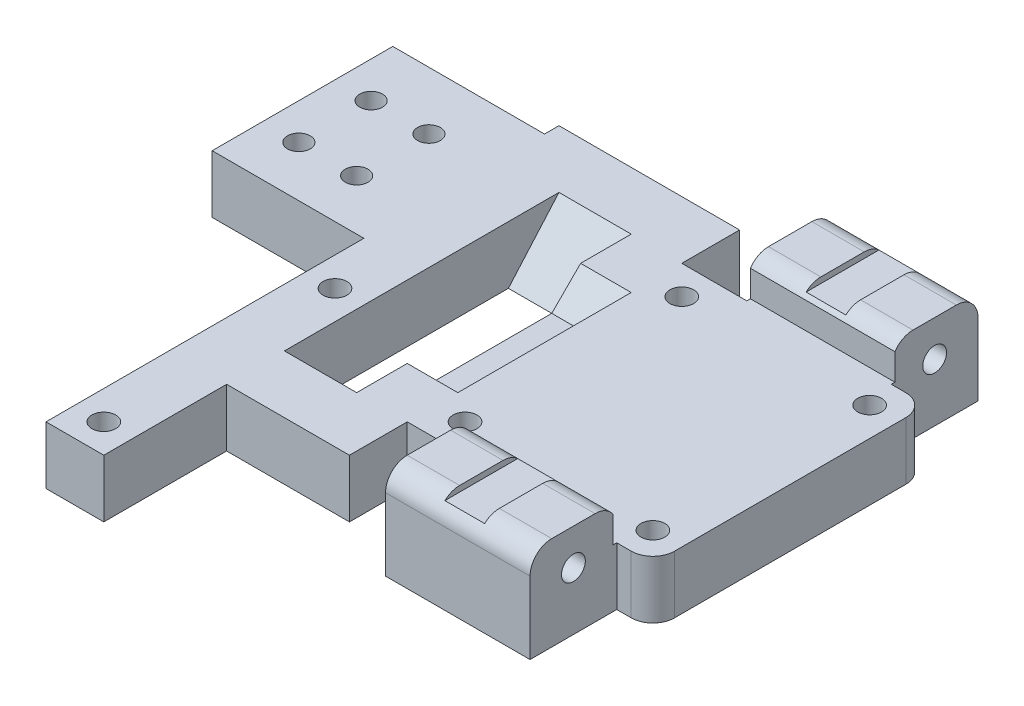
SolidWorks part; units mm, degrees
ref_plane "Front" through (0, 0, 0) normal (0, 0, 1) x (1, 0, 0)
ref_plane "Top" through (0, 0, 0) normal (0, 1, 0) x (1, 0, 0)
ref_plane "Right" through (0, 0, 0) normal (1, 0, 0) x (0, 0, -1)
sketch "Sketch1" plane through (0, 0, 0) normal (0, 1, 0) x (1, 0, 0)
  line L1 (0, 0) -> (300, 0)
  line L2 (0, 0) -> (0, -20)
  line L3 (0, -20) -> (300, -20)
  line L4 (300, 0) -> (300, -20)
  dimension "D1" = 20
  dimension "D2" = 300
extrude "Boss-Extrude1" add sketch "Sketch1" along normal blind 8
sketch "Sketch2" plane through (0, 0, 20) normal (0, 0, 1) x (1, 0, 0)
  line L0 (0, 8) -> (300, 8) construction
  line L1 (0, 0) -> (34, 0)
  line L2 (0, 0) -> (0, 8)
  line L3 (0, 8) -> (34, 8)
  line L4 (34, 0) -> (34, 8)
  line L5 (266, 8) -> (300, 8)
  line L6 (300, 0) -> (300, 8)
  line L7 (266, 0) -> (300, 0)
  line L8 (266, 0) -> (266, 8)
  dimension "D1" = 34
  dimension "D2" = 2
extrude "Boss-Extrude2" add sketch "Sketch2" along normal blind 9
sketch "Sketch3" plane through (0, 0, 0) normal (0, 0, -1) x (-1, 0, 0)
  line L0 (-300, 8) -> (0, 8) construction
  line L1 (0, 0) -> (-34, 0)
  line L2 (0, 0) -> (0, 8)
  line L3 (0, 8) -> (-34, 8)
  line L4 (-34, 0) -> (-34, 8)
  line L5 (-300, 0) -> (-300, 8)
  line L6 (-266, 8) -> (-300, 8)
  line L7 (-266, 0) -> (-266, 8)
  line L8 (-266, 0) -> (-300, 0)
  dimension "D1" = 34
  dimension "D2" = 2
extrude "Boss-Extrude3" add sketch "Sketch3" along normal blind 9
sketch "Sketch4" plane through (0, 8, 0) normal (0, 1, 0) x (1, 0, 0)
  line L0 (0, 9) -> (34, 9) construction
  line L1 (0, 9) -> (0, -29) construction
  circle A0 centre (4, 5) radius 1.65
  circle A1 centre (30, 5) radius 1.65
  circle A2 centre (30, -25) radius 1.65
  circle A3 centre (4, -25) radius 1.65
  circle A4 centre (296, -25) radius 1.65
  circle A5 centre (296, 5) radius 1.65
  circle A6 centre (270, -25) radius 1.65
  circle A7 centre (270, 5) radius 1.65
  dimension "D1" = 3.3
  dimension "D2" = 4
  dimension "D3" = 4
  dimension "D4" = 2
  dimension "D5" = 2
  dimension "D6" = 2
extrude "Cut-Extrude1" cut sketch "Sketch4" against normal through all
sketch "Sketch5" plane through (0, 0, 20) normal (0, 0, 1) x (1, 0, 0)
  line L0 (34, 8) -> (266, 8) construction
  line L1 (266, 0) -> (241, 0)
  line L2 (266, 0) -> (266, 8)
  line L3 (266, 8) -> (241, 8)
  line L4 (241, 0) -> (241, 8)
  dimension "D1" = 25
extrude "Boss-Extrude4" add sketch "Sketch5" along normal blind 17
sketch "Sketch6" plane through (0, 0, 0) normal (0, 0, -1) x (-1, 0, 0)
  line L0 (-266, 0) -> (-34, 0) construction
  line L1 (-266, 8) -> (-241, 8)
  line L2 (-266, 8) -> (-266, 0)
  line L3 (-266, 0) -> (-241, 0)
  line L4 (-241, 8) -> (-241, 0)
  dimension "D1" = 25
extrude "Boss-Extrude5" add sketch "Sketch6" along normal blind 17
sketch "Sketch7" plane through (0, 8, 0) normal (0, 1, 0) x (1, 0, 0)
  line L0 (266, -37) -> (241, -37) construction
  line L1 (259, -29) -> (249, -29)
  line L2 (259, -29) -> (259, 9)
  line L3 (259, 9) -> (249, 9)
  line L4 (249, -29) -> (249, 9)
  line L5 (241, -37) -> (241, -20) construction
  dimension "D1" = 10
  dimension "D2" = 38
  dimension "D3" = 8
  dimension "D4" = 8
extrude "Cut-Extrude2" cut sketch "Sketch7" against normal through all
sketch "Sketch8" plane through (0, 8, 0) normal (0, 1, 0) x (1, 0, 0)
  line L0 (259, -29) -> (259, 9) construction
  line L1 (259, -18) -> (266, -18)
  line L2 (259, -18) -> (259, -2)
  line L3 (259, -2) -> (266, -2)
  line L4 (266, -18) -> (266, -2)
  line L5 (266, -37) -> (241, -37) construction
  dimension "D1" = 7
  dimension "D2" = 16
  dimension "D3" = 19
extrude "Cut-Extrude3" cut sketch "Sketch8" against normal blind 4
sketch "Sketch9" plane through (259, 0, 0) normal (-1, 0, 0) x (0, 0, 1)
  line L0 (18, 4) -> (22, 8)
  line L1 (29, 8) -> (18, 8) construction
  line L2 (22, 8) -> (18, 8)
  line L3 (18, 8) -> (18, 4)
  line L4 (2, 4) -> (-2, 8)
  line L5 (2, 8) -> (-9, 8) construction
  line L6 (-2, 8) -> (2, 8)
  line L7 (2, 8) -> (2, 4)
  dimension "D1" = 4
  dimension "D2" = 4
extrude "Cut-Extrude4" cut sketch "Sketch9" against normal blind 7
sketch "Sketch10" plane through (259, 0, 0) normal (-1, 0, 0) x (0, 0, 1)
  line L0 (-9, 8) -> (-2, 0)
  line L1 (29, 0) -> (-9, 0) construction
  line L2 (-2, 0) -> (-9, 0)
  line L3 (-9, 0) -> (-9, 8)
  line L4 (29, 8) -> (22, 0)
  line L5 (22, 0) -> (29, 0)
  line L6 (29, 0) -> (29, 8)
  line L7 (-51.4523, 12.1971) -> (-51.8778, 12.5861)
  line M6 (-9, 8) -> (-9, 0)
  line M7 (-9, 0) -> (29, 0)
  line M8 (29, 0) -> (29, 8)
  dimension "D1" = 7
  dimension "D2" = 7
extrude "Boss-Extrude6" add sketch "Sketch10" along normal blind 10 contours L0 M6 M7 | L4 M8 M7
sketch "Sketch12" plane through (0, 0, 37) normal (0, 0, 1) x (1, 0, 0)
  line L0 (241, 0) -> (266, 0) construction
  line L1 (241, 8) -> (249, 8)
  line L2 (241, 8) -> (241, 0)
  line L3 (241, 0) -> (249, 0)
  line L4 (249, 8) -> (249, 0)
  dimension "D1" = 8
extrude "Boss-Extrude7" add sketch "Sketch12" along normal blind 17
sketch "Sketch13" plane through (0, 8, 0) normal (0, 1, 0) x (1, 0, 0)
  line L0 (249, -54) -> (241, -54) construction
  line L1 (249, -54) -> (249, -37) construction
  circle A0 centre (245, -50) radius 1.65
  circle A1 centre (245, -18) radius 1.65
  dimension "D1" = 3.3
  dimension "D2" = 4
  dimension "D3" = 4
  dimension "D4" = 2
extrude "Cut-Extrude6" cut sketch "Sketch13" against normal through all
sketch "Sketch14" plane through (0, 0, 29) normal (0, 0, 1) x (1, 0, 0)
  line L1 (295, 13) -> (275, 13)
  line L2 (295, 13) -> (295, 0)
  line L3 (295, 0) -> (275, 0)
  line L4 (275, 13) -> (275, 0)
  line L5 (266, 0) -> (300, 0) construction
  line L7 (266, 8) -> (266, 0) construction
  dimension "D1" = 20
  dimension "D2" = 9
  dimension "D3" = 13
extrude "Boss-Extrude8" add sketch "Sketch14" along normal blind 12
sketch "Sketch15" plane through (295, 0, 0) normal (1, 0, 0) x (0, 0, -1)
  line L0 (-41, 0) -> (-41, 13) construction
  line L1 (-41, 13) -> (-29, 13) construction
  circle A0 centre (-35, 8) radius 1.65
  dimension "D1" = 3.3
  dimension "D2" = 6
  dimension "D3" = 5
extrude "Cut-Extrude7" cut sketch "Sketch15" against normal blind 20
sketch "Sketch16" plane through (0, 0, -9) normal (0, 0, -1) x (-1, 0, 0)
  line L1 (-295, 13) -> (-275, 13)
  line L2 (-295, 13) -> (-295, 0)
  line L3 (-295, 0) -> (-275, 0)
  line L4 (-275, 13) -> (-275, 0)
  line L5 (-300, 0) -> (-266, 0) construction
  line L6 (-266, 0) -> (-266, 8) construction
  dimension "D1" = 20
  dimension "D2" = 9
  dimension "D3" = 13
extrude "Boss-Extrude9" add sketch "Sketch16" along normal blind 12
sketch "Sketch17" plane through (295, 0, 0) normal (1, 0, 0) x (0, 0, -1)
  line L1 (21, 13) -> (21, 0) construction
  line L2 (21, 13) -> (9, 13) construction
  circle A0 centre (15, 8) radius 1.65
  dimension "D1" = 3.3
  dimension "D3" = 6
  dimension "D2" = 5
extrude "Cut-Extrude8" cut sketch "Sketch17" against normal blind 20
sketch "Sketch18" plane through (0, 0, -9) normal (0, 0, -1) x (-1, 0, 0)
  line L1 (-25, 13) -> (-5, 13)
  line L2 (-25, 13) -> (-25, 0)
  line L3 (-25, 0) -> (-5, 0)
  line L4 (-5, 13) -> (-5, 0)
  line L5 (-34, 0) -> (0, 0) construction
  line L6 (-34, 8) -> (-34, 0) construction
  dimension "D1" = 20
  dimension "D2" = 9
  dimension "D3" = 13
extrude "Boss-Extrude10" add sketch "Sketch18" along normal blind 12
sketch "Sketch19" plane through (5, 0, 0) normal (-1, 0, 0) x (0, 0, 1)
  line L0 (-21, 0) -> (-21, 13) construction
  line L1 (-21, 13) -> (-9, 13) construction
  circle A0 centre (-15, 8) radius 1.6
  dimension "D1" = 3.2
  dimension "D2" = 6
  dimension "D3" = 5
extrude "Cut-Extrude9" cut sketch "Sketch19" against normal blind 20
sketch "Sketch20" plane through (0, 0, 29) normal (0, 0, 1) x (1, 0, 0)
  line L1 (5, 13) -> (25, 13)
  line L2 (5, 13) -> (5, 0)
  line L3 (5, 0) -> (25, 0)
  line L4 (25, 13) -> (25, 0)
  line L5 (0, 0) -> (34, 0) construction
  line L6 (34, 0) -> (34, 8) construction
  dimension "D1" = 20
  dimension "D2" = 9
  dimension "D3" = 13
extrude "Boss-Extrude11" add sketch "Sketch20" along normal blind 12
sketch "Sketch21" plane through (5, 0, 0) normal (-1, 0, 0) x (0, 0, 1)
  line L0 (41, 13) -> (41, 0) construction
  line L2 (41, 13) -> (29, 13) construction
  circle A0 centre (35, 8) radius 1.6
  dimension "D1" = 3.2
  dimension "D2" = 6
  dimension "D3" = 5
extrude "Cut-Extrude10" cut sketch "Sketch21" against normal blind 20
fillet "Fillet6" radius 3 8 edges at (15, 13, 41) (15, 13, 29) (15, 13, -9) (15, 13, -21) (285, 13, 41) (285, 13, 29) (285, 13, -9) (285, 13, -21)
sketch "Sketch28" plane through (0, 0, 0) normal (-1, 0, 0) x (0, 0, 1)
  line L1 (78.9453, 217.6934) -> (-119.9362, 217.6934)
  line L2 (78.9453, 217.6934) -> (78.9453, -338.6618)
  line L3 (78.9453, -338.6618) -> (-119.9362, -338.6618)
  line L4 (-119.9362, 217.6934) -> (-119.9362, -338.6618)
extrude "Cut-Extrude14" cut sketch "Sketch28" against normal blind 220
sketch "Sketch29" plane through (0, 0, 0) normal (0, 0, -1) x (-1, 0, 0)
  line L1 (-241, 0) -> (-220, 0)
  line L2 (-241, 0) -> (-241, 8)
  line L3 (-241, 8) -> (-220, 8)
  line L4 (-220, 0) -> (-220, 8)
extrude "Boss-Extrude12" add sketch "Sketch29" along normal blind 15
sketch "Sketch30" plane through (0, 0, 0) normal (0, -1, 0) x (-1, 0, 0)
  line L1 (-220, -20) -> (-241, -20)
  line L2 (-220, -20) -> (-220, -10)
  line L3 (-220, -10) -> (-241, -10)
  line L4 (-241, -20) -> (-241, -10)
  dimension "D1" = 21
  dimension "D2" = 10
extrude "Cut-Extrude15" cut sketch "Sketch30" against normal through all
sketch "Sketch31" plane through (0, 0, 0) normal (0, -1, 0) x (-1, 0, 0)
  line L0 (-220, -10) -> (-220, 15) construction
  line L1 (-241, 15) -> (-220, 15) construction
  line L2 (-220, -10) -> (-241, -10) construction
  circle A0 centre (-225, 7) radius 1.575
  circle A1 centre (-225, -3) radius 1.575
  circle A2 centre (-233, 7) radius 1.575
  circle A3 centre (-233, -3) radius 1.575
  dimension "D1" = 3.15
  dimension "D2" = 3.15
  dimension "D3" = 3.15
  dimension "D4" = 3.15
  dimension "D5" = 5
  dimension "D6" = 8
  dimension "D7" = 5
  dimension "D8" = 7
  dimension "D9" = 8
  dimension "D10" = 8
  dimension "D11" = 7
  dimension "D12" = 8
extrude "Cut-Extrude16" cut sketch "Sketch31" against normal through all
fillet "Fillet7" radius 3 2 edges at (300, 4, -9) (300, 4, 29)
sketch "Sketch32" plane through (0, 13, 0) normal (0, 1, 0) x (1, 0, 0)
  line L0 (295, -38) -> (295, -32) construction
  line L1 (287.75, -42.4531) -> (282.25, -42.4531)
  line L2 (287.75, -42.4531) -> (287.75, 28.0104)
  line L3 (287.75, 28.0104) -> (282.25, 28.0104)
  line L4 (282.25, -42.4531) -> (282.25, 28.0104)
  dimension "D1" = 5.5
  dimension "D2" = 7.25
extrude "Cut-Extrude17" cut sketch "Sketch32" against normal blind 0.8
sketch "Sketch33" plane through (0, 0, 29) normal (0, 0, -1) x (-1, 0, 0)
  line L1 (-275, 8) -> (-295, 8)
  line L2 (-275, 8) -> (-275, 12.9638)
  line L3 (-275, 12.9638) -> (-295, 12.9638)
  line L4 (-295, 8) -> (-295, 12.9638)
  dimension "D1" = 20
extrude "Cut-Extrude18" cut sketch "Sketch33" against normal blind 0.5
sketch "Sketch34" plane through (0, 0, -9) normal (0, 0, 1) x (1, 0, 0)
  line L1 (275, 8) -> (295, 8)
  line L2 (275, 8) -> (275, 19.9424)
  line L3 (275, 19.9424) -> (295, 19.9424)
  line L4 (295, 8) -> (295, 19.9424)
  dimension "D1" = 20
extrude "Cut-Extrude19" cut sketch "Sketch34" against normal blind 0.5
equation "\"滑动-垂直孔\" = 0.6"
equation "\"滑动-水平孔\"= 0.3"
equation "\"松动-垂直孔\" = 0.3"
equation "\"松动-水平孔\"= 0.1"
equation "\"正常-垂直孔\" = 0.15"
equation "\"正常-水平孔\"= 0"
equation "\"紧缩-垂直孔\"= 0"
equation "\"紧缩-水平孔\"= - 0.1"
equation "\"D4@Sketch31\"=\"正常-垂直孔\"+3"
equation "\"D3@Sketch31\"=\"正常-垂直孔\"+3"
equation "\"D1@Sketch31\"=\"正常-垂直孔\"+3"
equation "\"D2@Sketch31\"=\"正常-垂直孔\"+3"
equation "\"D1@Sketch13\"=\"松动-垂直孔\"+3"
equation "\"D1@Sketch4\"=\"松动-垂直孔\"+3"
equation "\"D1@Sketch17\"=\"滑动-水平孔\"+3"
equation "\"D1@Sketch15\"=\"滑动-水平孔\"+3"
